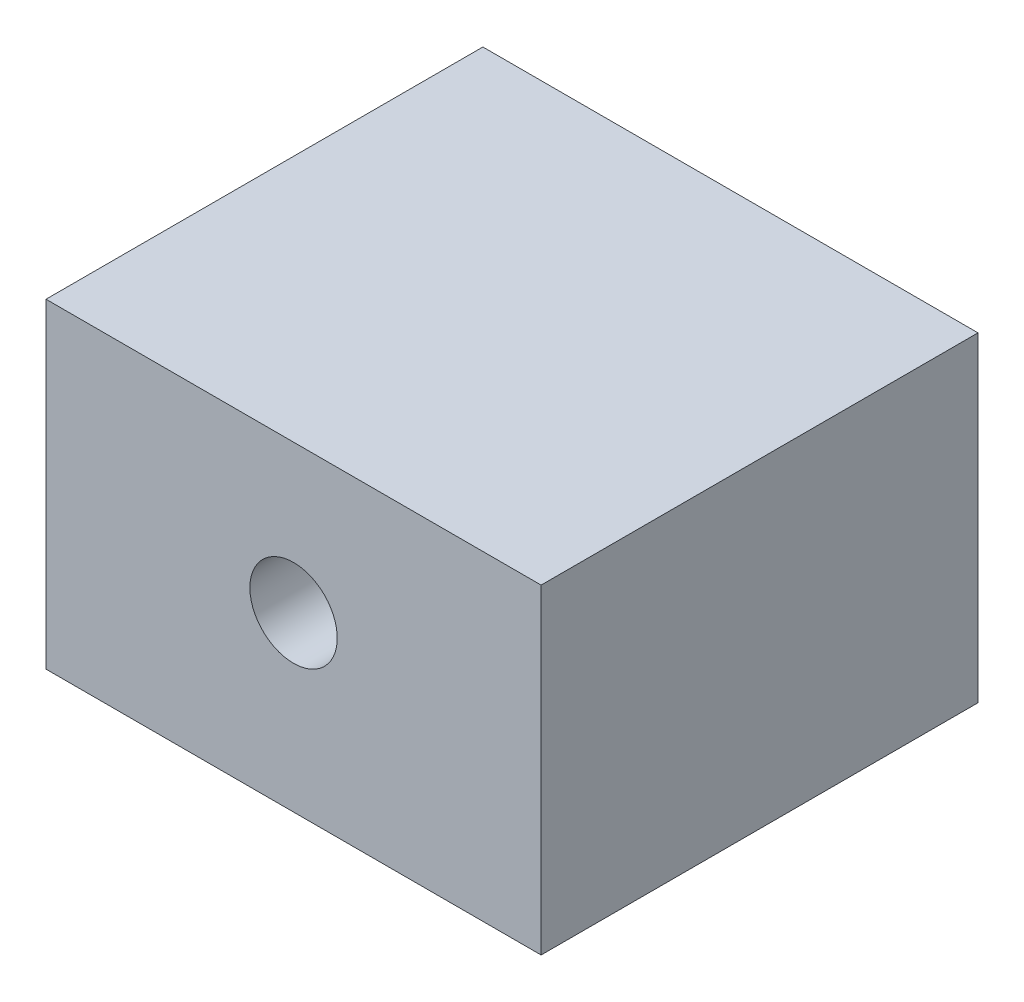
SolidWorks part; units mm, degrees
ref_plane "前视基准面" through (0, 0, 0) normal (0, 0, 1) x (1, 0, 0)
ref_plane "上视基准面" through (0, 0, 0) normal (0, 1, 0) x (1, 0, 0)
ref_plane "右视基准面" through (0, 0, 0) normal (1, 0, 0) x (0, 0, -1)
other "Configuration Table"
sketch "草图1" plane through (0, 0, 0) normal (0, 1, 0) x (1, 0, 0)
  line L1 (-17, 15) -> (17, 15)
  line L2 (-17, 15) -> (-17, -15)
  line L3 (-17, -15) -> (17, -15)
  line L4 (17, 15) -> (17, -15)
  line L5 (-17, 15) -> (17, -15) construction
  line L6 (-17, -15) -> (17, 15) construction
  point P0 (0, 0)
  dimension "D1" = 34
  dimension "D2" = 30
extrude "凸台-拉伸1" add sketch "草图1" along normal blind 22
sketch "草图2" plane through (2, 0, 15) normal (0, 0, -1) x (-1, 0, 0)
  line L0 (19, 22) -> (19, 0) construction
  circle A0 centre (2, 11.8463) radius 6
  circle A1 centre (2, 11.8463) radius 3
  dimension "D1" = 17
extrude "切除-拉伸1" cut sketch "草图2" along normal through all contours A1
sketch "草图3" plane through (0, 0, 0) normal (0, -1, 0) x (1, 0, 0)
  line L0 (17, 15) -> (17, -15) construction
  line L1 (-17, 15) -> (17, 15) construction
  line L2 (-17, -15) -> (-17, 15) construction
  line L3 (17, -15) -> (-17, -15) construction
  circle A0 centre (12, 9) radius 2.1
  circle A1 centre (12, -9) radius 2.1
  circle A2 centre (-12, 9) radius 2.1
  circle A3 centre (-12, -9) radius 2.1
  dimension "D1" = 5
  dimension "D2" = 6
  dimension "D3" = 6
  dimension "D4" = 5
  dimension "D5" = 5
  dimension "D6" = 6
  dimension "D7" = 6
  dimension "D8" = 5
extrude "切除-拉伸2" cut sketch "草图3" against normal blind 10
